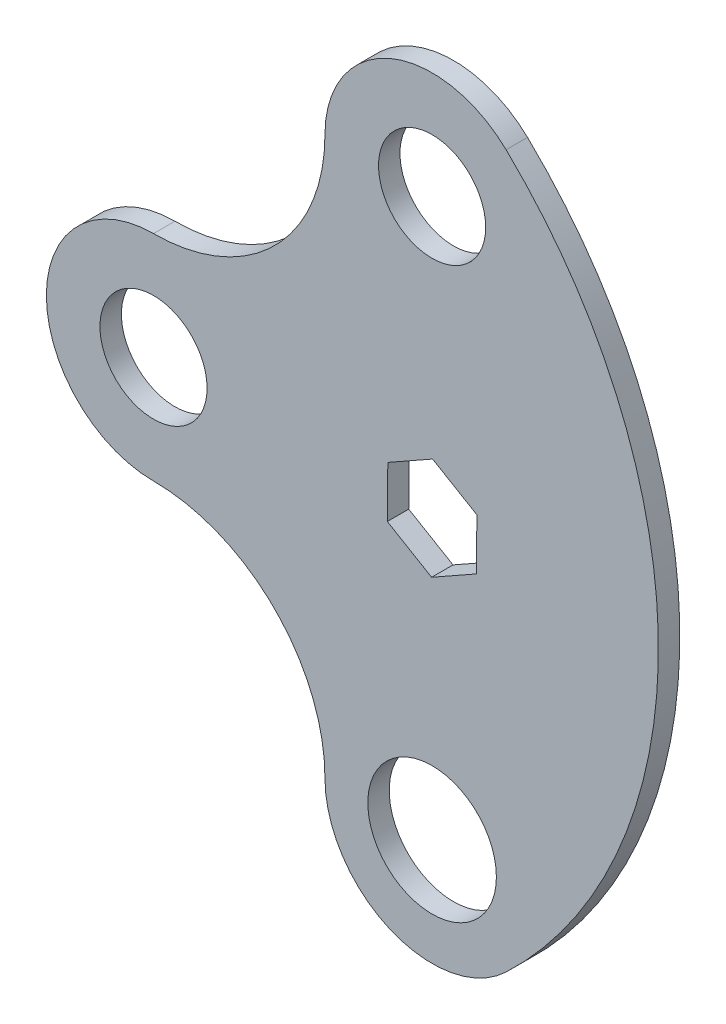
SolidWorks part; units mm, degrees
ref_plane "Front Plane" through (0, 0, 0) normal (0, 0, 1) x (1, 0, 0)
ref_plane "Top Plane" through (0, 0, 0) normal (0, 1, 0) x (1, 0, 0)
ref_plane "Right Plane" through (0, 0, 0) normal (1, 0, 0) x (0, 0, -1)
sketch "Sketch2" plane through (0, 0, 0) normal (0, 0, 1) x (1, 0, 0)
  line L0 (0, 0) -> (65, 0) construction
  line L2 (65, 0) -> (65, 65) construction
  line L4 (65, 0) -> (65, -65) construction
  line L5 (0, 0) -> (0, 65) construction
  line L6 (75.3349, -6.0983) -> (75.4487, 5.9012)
  line L7 (75.4487, 5.9012) -> (65.1138, 11.9995)
  line L8 (65.1138, 11.9995) -> (54.6651, 6.0983)
  line L9 (54.6651, 6.0983) -> (54.5513, -5.9012)
  line L10 (54.5513, -5.9012) -> (64.8862, -11.9995)
  line L11 (64.8862, -11.9995) -> (75.3349, -6.0983)
  line L12 (0, 0) -> (0, -65) construction
  arc A0 (0, 25) -> (0, -25) centre (0, 0) ccw
  circle A1 centre (0, 0) radius 12.5
  arc A2 (82.2679, 83.0781) -> (40, 65) centre (65, 65) ccw
  circle A3 centre (65, 65) radius 12.5
  arc A4 (40, -65) -> (82.2679, -83.0781) centre (65, -65) ccw
  circle A5 centre (65, -65) radius 15
  circle A6 centre (65, 0) radius 10.3923 construction
  arc A7 (0, 25) -> (40, 65) centre (0, 65) ccw
  arc A8 (40, -65) -> (0, -25) centre (0, -65) ccw
  arc A9 (82.2679, -83.0781) -> (82.2679, 83.0781) centre (2.9132, 0) ccw
  point P25 (0, 0)
  point P26 (0, 0)
  point P27 (2.9132, 0)
extrude "Boss-Extrude1" add sketch "Sketch2" along normal blind 5
